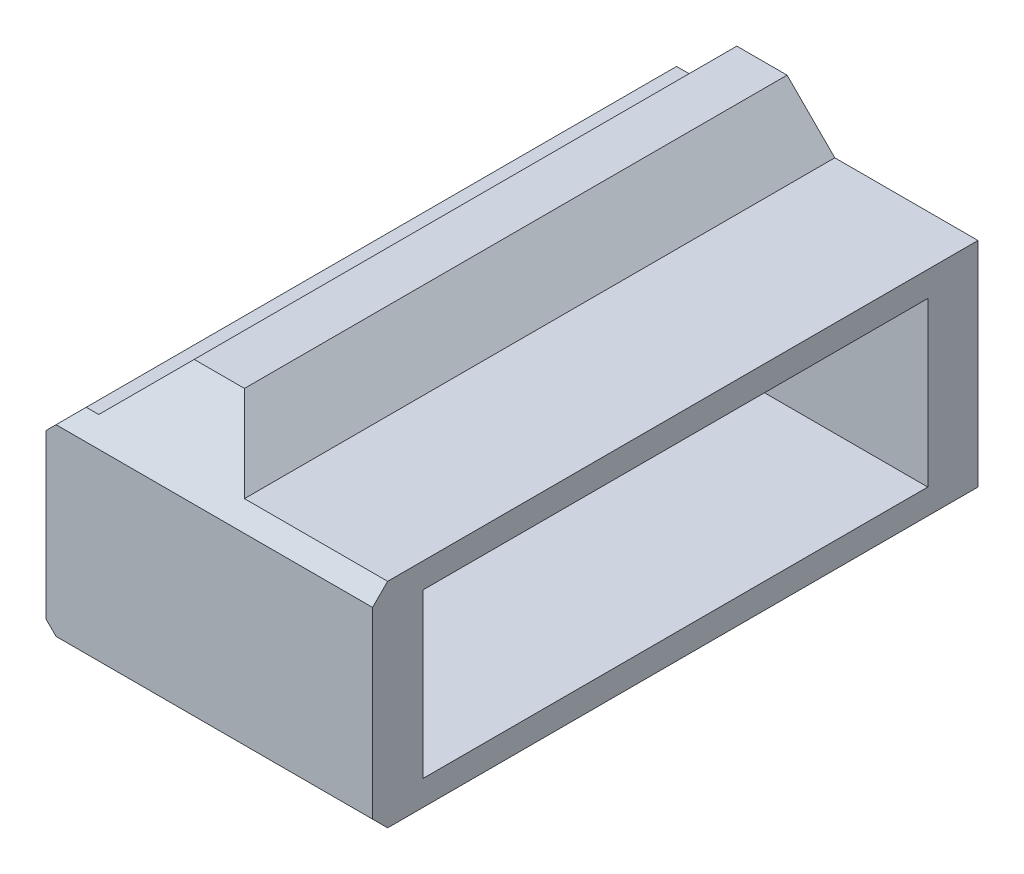
SolidWorks part; units mm, degrees
ref_plane "Front Plane" through (0, 0, 0) normal (0, 0, 1) x (1, 0, 0)
ref_plane "Top Plane" through (0, 0, 0) normal (0, 1, 0) x (1, 0, 0)
ref_plane "Right Plane" through (0, 0, 0) normal (1, 0, 0) x (0, 0, -1)
sketch "Sketch1" plane through (0, 0, 0) normal (0, 0, 1) x (1, 0, 0)
  line L0 (0, 8.5) -> (1.5, 8.5)
  line L1 (1.5, 8.5) -> (3.4, 10.4)
  line L2 (3.4, 10.4) -> (5.4, 10.4)
  line L3 (5.4, 10.4) -> (7.3, 8.5)
  line L4 (7.3, 8.5) -> (13, 8.5)
  line L5 (13, 8.5) -> (13, 0)
  line L6 (13, 0) -> (7.3, 0)
  line L7 (7.3, 0) -> (5.4, -1.9)
  line L8 (5.4, -1.9) -> (3.4, -1.9)
  line L9 (3.4, -1.9) -> (1.5, 0)
  line L10 (1.5, 0) -> (0, 0)
  line L11 (0, 0) -> (0, 8.5)
  line L12 (1.5, 8.5) -> (1.5, 0) construction
  line L13 (3.4, 10.4) -> (3.4, -1.9) construction
  line L14 (5.4, 10.4) -> (5.4, -1.9) construction
  line L15 (7.3, 8.5) -> (7.3, 0) construction
  line L16 (1.5, 8.5) -> (7.3, 8.5) construction
  line L17 (1.5, 0) -> (7.3, 0) construction
  dimension "D1" = 8.5
  dimension "D2" = 1.5
  dimension "D3" = 135
  dimension "D4" = 3.4
  dimension "D5" = 5.4
  dimension "D6" = 13
extrude "Boss-Extrude1" add sketch "Sketch1" along normal blind 24.1
sketch "Sketch2" plane through (13, 0, 0) normal (1, 0, 0) x (0, 0, -1)
  line L0 (-24.1, 8.5) -> (0, 8.5) construction
  line L1 (-22.1, 7.5) -> (-2, 7.5)
  line L2 (-22.1, 7.5) -> (-22.1, 1)
  line L3 (-22.1, 1) -> (-2, 1)
  line L4 (-2, 7.5) -> (-2, 1)
  line L5 (-24.1, 0) -> (-24.1, 8.5) construction
  dimension "D1" = 20.1
  dimension "D2" = 6.5
  dimension "D3" = 1
  dimension "D4" = 2
extrude "Cut-Extrude1" cut sketch "Sketch2" against normal blind 9.65
sketch "Sketch3" plane through (3.35, 0, 0) normal (1, 0, 0) x (0, 0, -1)
  line L0 (-22.1, 4.25) -> (-2, 4.25) construction
  line L1 (-22.1, 7.5) -> (-22.1, 1) construction
  line L2 (-2, 1) -> (-2, 7.5) construction
  line L3 (-5.5, 5.75) -> (-4, 5.75)
  line L4 (-20.5, 5.75) -> (-19, 5.75)
  line L5 (-20.5, 5.75) -> (-20.5, 2.75)
  line L6 (-20.5, 2.75) -> (-19, 2.75)
  line L7 (-19, 5.75) -> (-19, 2.75)
  line L8 (-5.5, 5.75) -> (-5.5, 2.75)
  line L9 (-5.5, 2.75) -> (-4, 2.75)
  line L10 (-4, 5.75) -> (-4, 2.75)
  line L11 (-19.75, 5.75) -> (-19.75, 2.75) construction
  line L12 (-11.5, 2.75) -> (-13, 2.75)
  line L13 (-11.5, 2.75) -> (-11.5, 5.75)
  line L14 (-11.5, 5.75) -> (-13, 5.75)
  line L15 (-13, 2.75) -> (-13, 5.75)
  line L16 (-11.5, 2.75) -> (-13, 5.75) construction
  line L17 (-11.5, 5.75) -> (-13, 2.75) construction
  line L18 (-4.75, 5.75) -> (-4.75, 2.75) construction
  line L19 (-12.25, 4.25) -> (-12.25, 7.1717) construction
  point P14 (-12.25, 4.25)
  dimension "D1" = 1.5
  dimension "D2" = 2.35
  dimension "D3" = 3
  dimension "D4" = 1.5
  dimension "D5" = 15
  dimension "D6" = 7.5
  dimension "D7" = 1.5
  dimension "D8" = 3
  dimension "D9" = 1.5
extrude "Cut-Extrude2" cut sketch "Sketch3" against normal through all
sketch "Sketch4" plane through (0, 0, 0) normal (-1, 0, 0) x (0, 0, 1)
  line L0 (5, 8.5) -> (5, 0) construction
  line L1 (24.1, 8.5) -> (0, 8.5) construction
  line L2 (24.1, 0) -> (0, 0) construction
  line L4 (0, 4.25) -> (24.1, 4.25) construction
  line L5 (0, 8.5) -> (0, 0) construction
  line L6 (24.1, 8.5) -> (24.1, 0) construction
  line L7 (19.1, 8.5) -> (19.1, 0) construction
  line L8 (24.1, 8.5) -> (0, 8.5) construction
  line L9 (24.1, 0) -> (0, 0) construction
  line L10 (19, 2.75) -> (19, 5.75) construction
  circle A0 centre (8, 4.25) radius 3
  circle A1 centre (16.5, 4.25) radius 3
  dimension "D2" = 6
  dimension "D4" = 6
  dimension "D5" = 8.5
  dimension "D1" = 8
  dimension "D3" = 0.1
extrude "Cut-Extrude3" cut sketch "Sketch4" against normal blind 2.8
sketch "Sketch5" plane through (0, 0, 0) normal (-1, 0, 0) x (0, 0, 1)
  line L0 (24.1, -1.9) -> (24.1, 0.6)
  line L1 (24.1, 8.5) -> (24.1, 0) construction
  line L2 (24.1, 0.6) -> (21.6, -1.9)
  line L3 (24.1, -1.9) -> (0, -1.9) construction
  line L4 (21.6, -1.9) -> (24.1, -1.9)
  line L5 (21.6, 10.4) -> (24.1, 10.4)
  line L6 (24.1, 10.4) -> (0, 10.4) construction
  line L7 (24.1, 10.4) -> (24.1, 7.9)
  line L8 (24.1, 7.9) -> (21.6, 10.4)
  dimension "D1" = 2.5
  dimension "D2" = 2.5
  dimension "D3" = 2.5
  dimension "D4" = 2.5
extrude "Cut-Extrude4" cut sketch "Sketch5" against normal through all
chamfer "Chamfer1" distance 1 angle 45 2 edges at (0, 8.5, 11.75) (0, 0, 11.75)
